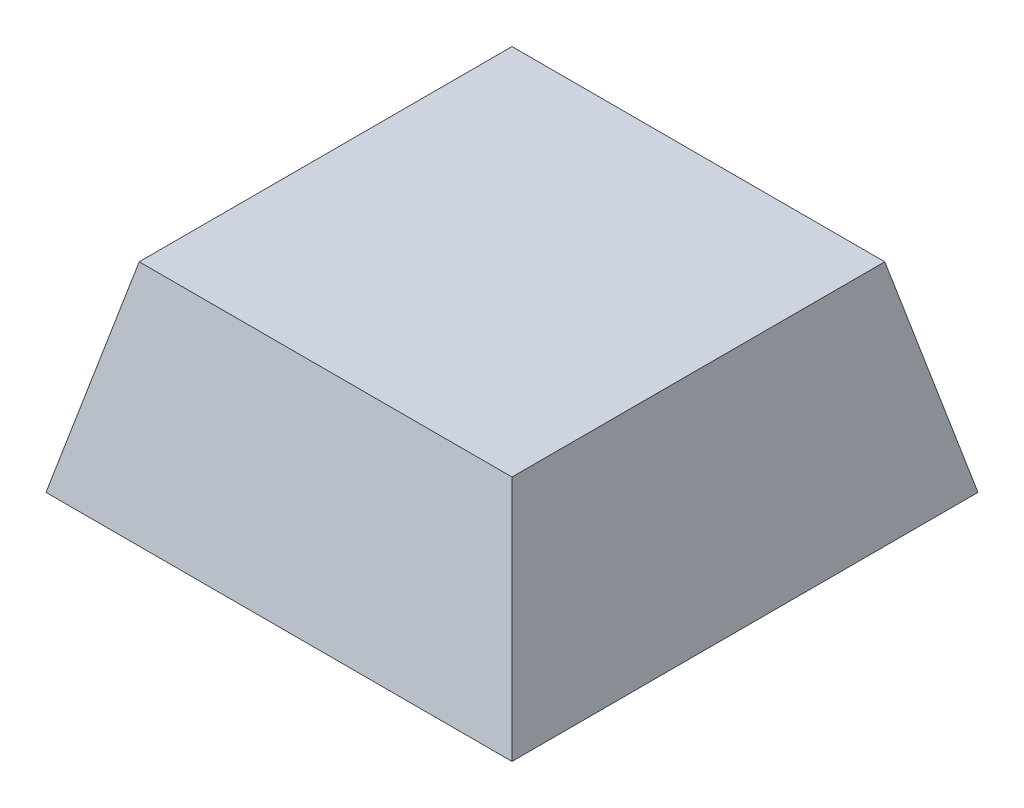
SolidWorks part; units mm, degrees
ref_plane "Front Plane" through (0, 0, 0) normal (0, 0, 1) x (1, 0, 0)
ref_plane "Top Plane" through (0, 0, 0) normal (0, 1, 0) x (1, 0, 0)
ref_plane "Right Plane" through (0, 0, 0) normal (1, 0, 0) x (0, 0, -1)
sketch "Sketch1" plane through (0, 0, 0) normal (0, 1, 0) x (1, 0, 0)
  line L1 (0, 0) -> (7, 0)
  line L2 (0, 0) -> (0, 7)
  line L3 (0, 7) -> (7, 7)
  line L4 (7, 0) -> (7, 7)
  dimension "D1" = 7
  dimension "D2" = 7
extrude "Boss-Extrude1" add sketch "Sketch1" along normal blind 3
sketch "Sketch2" plane through (0, 0, 0) normal (0, 0, 1) x (1, 0, 0)
  line L0 (0, 0) -> (0.7, 3)
  line L1 (0, 3) -> (7, 3) construction
  line L2 (0.7, 3) -> (0, 3)
  line L3 (0, 3) -> (0, 0)
  line L4 (7, 0) -> (6.3, 3)
  line L5 (6.3, 3) -> (7, 3)
  line L6 (7, 3) -> (7, 0)
  dimension "D1" = 0.7
  dimension "D2" = 0.7
extrude "Cut-Extrude1" cut sketch "Sketch2" against normal blind 7
sketch "Sketch3" plane through (0, 0, 0) normal (1, 0, 0) x (0, 0, -1)
  line L0 (0, 0) -> (0.7, 3)
  line L1 (7, 3) -> (0, 3) construction
  line L2 (0.7, 3) -> (0, 3)
  line L3 (0, 3) -> (0, 0)
  line L4 (7, 3) -> (6.3, 3)
  line L5 (6.3, 3) -> (7, 0)
  line L6 (7, 3) -> (7, 0)
  dimension "D1" = 0.7
  dimension "D2" = 0.7
extrude "Cut-Extrude2" cut sketch "Sketch3" along normal blind 11
sketch "Sketch4" plane through (0, 0, 0) normal (0, -1, 0) x (1, 0, 0)
  line L0 (3.5, 0) -> (3.5, -7) construction
  line L1 (0, 0) -> (7, 0) construction
  line L2 (7, -7) -> (0, -7) construction
  line L3 (0, -3.5) -> (7, -3.5) construction
  line L4 (0, -7) -> (0, 0) construction
  line L5 (7, 0) -> (7, -7) construction
  circle A0 centre (3.5, -3.5) radius 1.8
  dimension "D1" = 3.6
extrude "Cut-Extrude3" cut sketch "Sketch4" against normal blind 0.8
